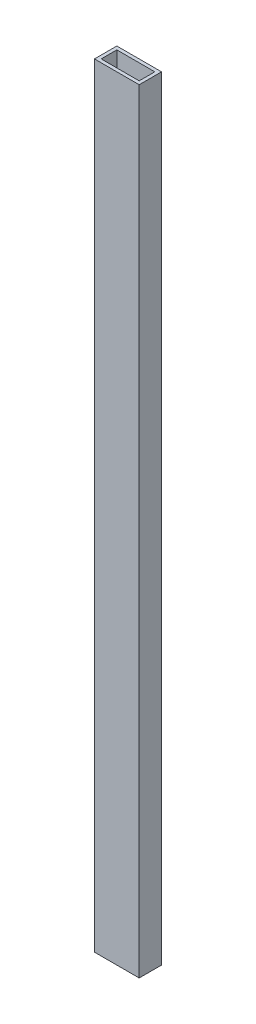
SolidWorks part; units mm, degrees
ref_plane "Front Plane" through (0, 0, 0) normal (0, 0, 1) x (1, 0, 0)
ref_plane "Top Plane" through (0, 0, 0) normal (0, 1, 0) x (1, 0, 0)
ref_plane "Right Plane" through (0, 0, 0) normal (1, 0, 0) x (0, 0, -1)
sketch "Sketch1" plane through (0, 0, 0) normal (0, 1, 0) x (1, 0, 0)
  line L1 (10, -5) -> (-10, -5)
  line L2 (10, -5) -> (10, 5)
  line L3 (10, 5) -> (-10, 5)
  line L4 (-10, -5) -> (-10, 5)
  line L5 (10, -5) -> (-10, 5) construction
  line L6 (10, 5) -> (-10, -5) construction
  point P0 (0, 0)
extrude "Boss-Extrude1" add sketch "Sketch1" along normal up to surface (346 mm away)
sketch "Sketch2" plane through (0, 0, 0) normal (0, -1, 0) x (1, 0, 0)
  line L1 (8.5, 3.5) -> (-8.5, 3.5)
  line L2 (8.5, 3.5) -> (8.5, -3.5)
  line L3 (8.5, -3.5) -> (-8.5, -3.5)
  line L4 (-8.5, 3.5) -> (-8.5, -3.5)
  line L5 (8.5, 3.5) -> (-8.5, -3.5) construction
  line L6 (8.5, -3.5) -> (-8.5, 3.5) construction
  point P0 (0, 0)
extrude "Cut-Extrude1" cut sketch "Sketch2" against normal through all
